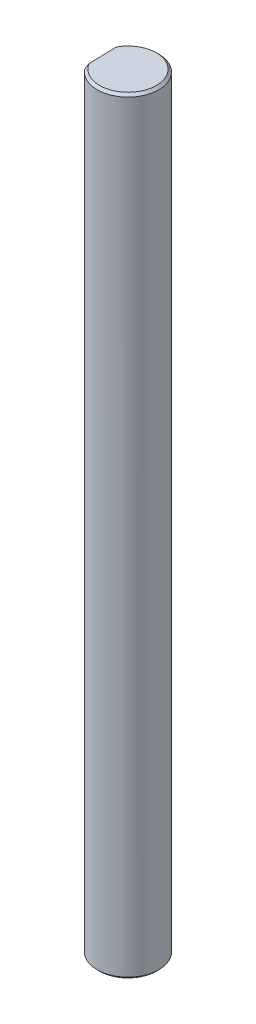
SolidWorks part; units mm, degrees
ref_plane "Front Plane" through (0, 0, 0) normal (0, 0, 1) x (1, 0, 0)
ref_plane "Top Plane" through (0, 0, 0) normal (0, 1, 0) x (1, 0, 0)
ref_plane "Right Plane" through (0, 0, 0) normal (1, 0, 0) x (0, 0, -1)
sketch "Sketch1" plane through (0, 0, 0) normal (0, 1, 0) x (1, 0, 0)
  circle A0 centre (0, 0) radius 2.5
  dimension "D1" = 5
extrude "Boss-Extrude1" add sketch "Sketch1" along normal blind 62.2
sketch "Sketch2" plane through (0, 62.2, 0) normal (0, 1, 0) x (1, 0, 0)
  line L0 (-2.0393, 1.4461) -> (-1.9593, -1.5528)
  circle A0 centre (0, 0) radius 2.5 construction
  circle A2 centre (0, 0) radius 2.5
  arc A3 (-2.0393, 1.4461) -> (-1.9593, -1.5528) centre (0, 0) ccw
  dimension "D2" = 2
  dimension "D1" = 0
extrude "Cut-Extrude1" cut sketch "Sketch2" against normal blind 20 and the other way through all
chamfer "Chamfer1" distance 0.2 angle 45 1 edges at (2.4991, 62.2, -0.0667)
chamfer "Chamfer2" distance 0.2 angle 45 1 edges at (0, 0, 2.5)
